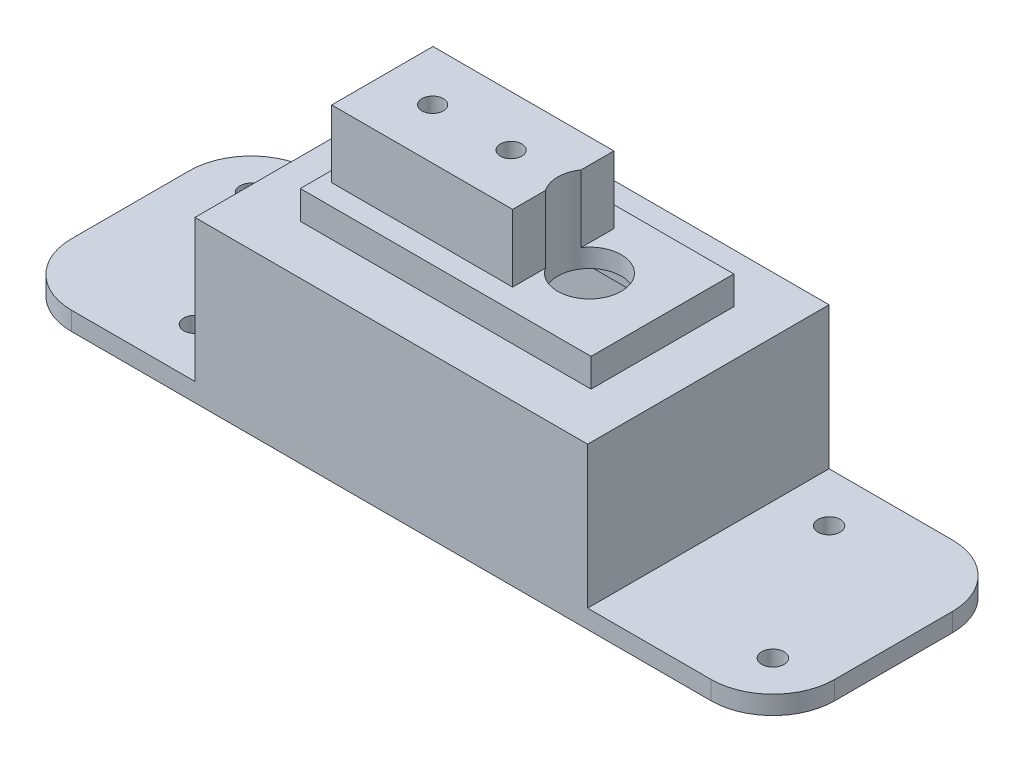
SolidWorks part; units mm, degrees
ref_plane "Front Plane" through (0, 0, 0) normal (0, 0, 1) x (1, 0, 0)
ref_plane "Top Plane" through (0, 0, 0) normal (0, 1, 0) x (1, 0, 0)
ref_plane "Right Plane" through (0, 0, 0) normal (1, 0, 0) x (0, 0, -1)
sketch "Sketch1" plane through (0, 0, 0) normal (0, 1, 0) x (1, 0, 0)
  line L1 (0, 0) -> (63.6, 0)
  line L2 (0, 0) -> (0, 39.1)
  line L3 (0, 39.1) -> (63.6, 39.1)
  line L4 (63.6, 0) -> (63.6, 39.1)
  dimension "D1" = 39.1
  dimension "D2" = 63.6
extrude "Boss-Extrude1" add sketch "Sketch1" along normal blind 23 contours L3 L4 L1 L2
sketch "Sketch3" plane through (0, 23, 0) normal (0, 1, 0) x (1, 0, 0)
  line L0 (0, 0) -> (0, 39.1) construction
  line L1 (9.08, 7.99) -> (56.16, 7.99)
  line L2 (9.08, 7.99) -> (9.08, 31.11)
  line L3 (9.08, 31.11) -> (56.16, 31.11)
  line L4 (56.16, 7.99) -> (56.16, 31.11)
  line L5 (9.08, 7.99) -> (56.16, 31.11) construction
  line L6 (9.08, 31.11) -> (56.16, 7.99) construction
  line L7 (63.6, 0) -> (63.6, 39.1) construction
  line L8 (0, 39.1) -> (63.6, 39.1) construction
  line L9 (0, 0) -> (63.6, 0) construction
  point P0 (32.62, 19.55)
  dimension "D1" = 9.08
  dimension "D2" = 7.44
  dimension "D3" = 7.99
  dimension "D4" = 7.99
extrude "Boss-Extrude2" add sketch "Sketch3" along normal blind 4.6 contours L3 L4 L1 L2
sketch "Sketch4" plane through (0, 27.6, 0) normal (0, 1, 0) x (1, 0, 0)
  line L1 (10.8, 11.35) -> (40.1, 11.35)
  line L2 (10.8, 11.35) -> (10.8, 27.75)
  line L3 (10.8, 27.75) -> (40.1, 27.75)
  line L4 (40.1, 11.35) -> (40.1, 27.75)
  line L7 (0, 0) -> (0, 39.1) construction
  line L8 (63.6, 0) -> (63.6, 39.1) construction
  line L9 (0, 39.1) -> (63.6, 39.1) construction
  line L10 (0, 0) -> (63.6, 0) construction
  dimension "D1" = 10.8
  dimension "D2" = 23.5
  dimension "D3" = 11.35
  dimension "D4" = 11.35
extrude "Boss-Extrude3" add sketch "Sketch4" along normal blind 10.9
shell "Shell1" thickness 3
sketch "Sketch5" plane through (0, 0, 0) normal (0, -1, 0) x (1, 0, 0)
  line L0 (63.6, 0) -> (63.6, -39.1) construction
  line L1 (93.6, 0) -> (-30, 0)
  line L2 (93.6, 0) -> (93.6, -39.1)
  line L3 (93.6, -39.1) -> (-30, -39.1)
  line L4 (-30, 0) -> (-30, -39.1)
  line L5 (0, 0) -> (0, -39.1) construction
  line L6 (0, -39.1) -> (63.6, -39.1) construction
  line L7 (0, 0) -> (63.6, 0) construction
  dimension "D1" = 30
  dimension "D2" = 30
  dimension "D3" = 0
  dimension "D4" = 0
extrude "Boss-Extrude4" add sketch "Sketch5" along normal blind 3
sketch "Sketch6" plane through (0, 38.5, 0) normal (0, 1, 0) x (1, 0, 0)
  line L0 (0, 0) -> (0, 39.1) construction
  line L2 (10.8, 11.35) -> (40.1, 11.35) construction
  circle A0 centre (18.95, 19.55) radius 1.73
  circle A1 centre (31.65, 19.55) radius 1.73
  dimension "D3" = 3.46
  dimension "D4" = 3.46
  dimension "D1" = 18.95
  dimension "D2" = 12.7
  dimension "D5" = 8.2
  dimension "D6" = 8.2
extrude "Cut-Extrude1" cut sketch "Sketch6" against normal through all
sketch "Sketch7" plane through (0, -3, 0) normal (0, -1, 0) x (1, 0, 0)
  line L0 (-30, -39.1) -> (93.6, -39.1) construction
  line L1 (60.6, -36.1) -> (3, -36.1)
  line L2 (60.6, -36.1) -> (60.6, -3)
  line L3 (60.6, -3) -> (3, -3)
  line L4 (3, -36.1) -> (3, -3)
  line L5 (93.6, 0) -> (-30, 0) construction
  line L6 (-30, 0) -> (-30, -39.1) construction
  line L7 (93.6, -39.1) -> (93.6, 0) construction
  dimension "D1" = 3
  dimension "D2" = 3
  dimension "D3" = 33
  dimension "D4" = 33
extrude "Cut-Extrude2" cut sketch "Sketch7" against normal blind 3
sketch "Sketch8" plane through (0, 0, 0) normal (0, 1, 0) x (1, 0, 0)
  line L0 (93.6, 0) -> (63.6, 0) construction
  line L1 (93.6, 39.1) -> (93.6, 0) construction
  line L2 (63.6, 0) -> (63.6, 39.1) construction
  line L3 (63.6, 39.1) -> (93.6, 39.1) construction
  line L4 (0, 0) -> (-30, 0) construction
  line L5 (0, 0) -> (0, 39.1) construction
  line L6 (-30, 0) -> (-30, 39.1) construction
  line L7 (-30, 39.1) -> (0, 39.1) construction
  circle A0 centre (85.6, 8) radius 1.8
  circle A1 centre (71.6, 31.1) radius 1.8
  circle A2 centre (-8, 8) radius 1.8
  circle A3 centre (-22, 31.1) radius 1.8
  dimension "D1" = 8
  dimension "D2" = 8
  dimension "D3" = 8
  dimension "D4" = 8
  dimension "D7" = 8
  dimension "D8" = 8
  dimension "D9" = 3.6
  dimension "D10" = 3.6
  dimension "D11" = 3.6
  dimension "D12" = 3.6
  dimension "D5" = 8
  dimension "D6" = 8
extrude "Cut-Extrude3" cut sketch "Sketch8" against normal blind 3
fillet "Fillet1" radius 10 4 edges at (-30, -1.5, -39.1) (-30, -1.5, 0) (93.6, -1.5, 0) (93.6, -1.5, -39.1)
sketch "Sketch9" plane through (0, 27.6, 0) normal (0, 1, 0) x (1, 0, 0)
  circle A0 centre (44.35, 19.55) radius 5.15
  circle A2 centre (31.65, 19.55) radius 1.73 construction
  dimension "D1" = 10.3
  dimension "D2" = 12.7
  dimension "D3" = 0
extrude "Cut-Extrude4" cut sketch "Sketch9" against normal blind 10
sketch "Sketch12" plane through (0, 38.5, 0) normal (0, 1, 0) x (1, 0, 0)
  circle A0 centre (44.35, 19.55) radius 5.15
  circle A1 centre (31.65, 19.55) radius 1.73 construction
  dimension "D1" = 10.3
  dimension "D2" = 12.7
  dimension "D3" = 0
extrude "Cut-Extrude5" cut sketch "Sketch12" against normal through all
